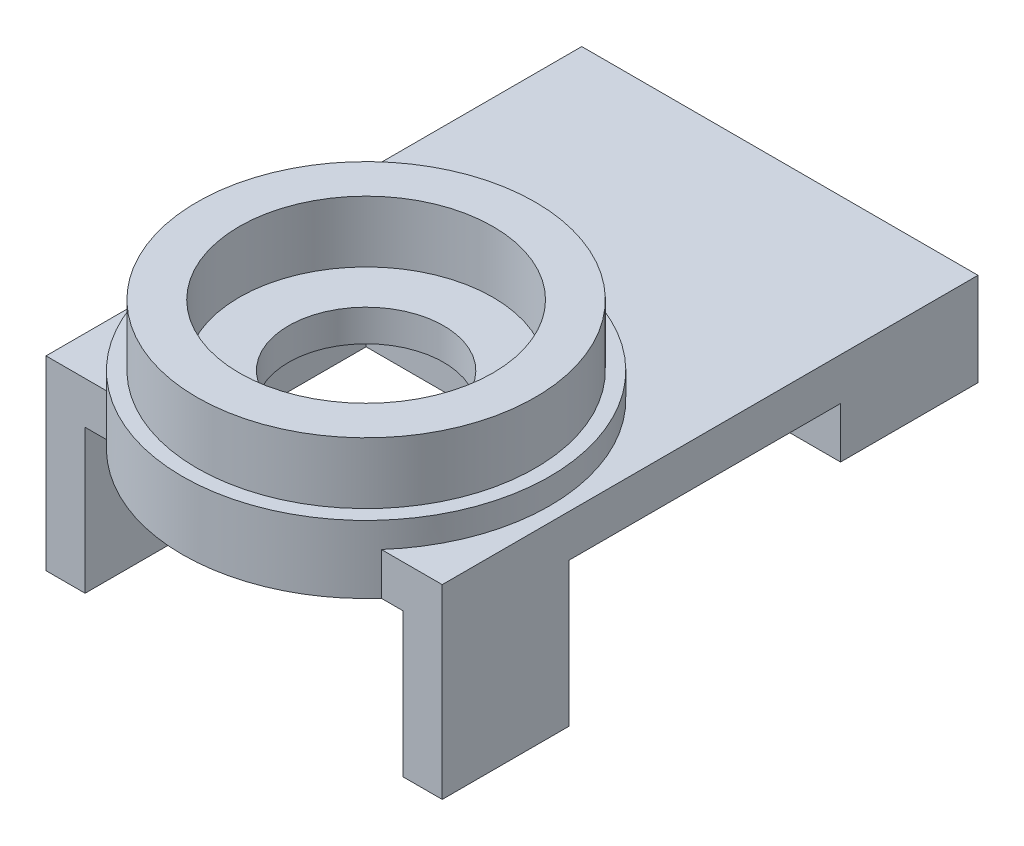
SolidWorks part; units mm, degrees
ref_plane "Front Plane" through (0, 0, 0) normal (0, 0, 1) x (1, 0, 0)
ref_plane "Top Plane" through (0, 0, 0) normal (0, 1, 0) x (1, 0, 0)
ref_plane "Right Plane" through (0, 0, 0) normal (1, 0, 0) x (0, 0, -1)
sketch "Sketch2" plane through (0, 0, 0) normal (0, 1, 0) x (1, 0, 0)
  line L1 (-2.1351, -6.1488) -> (6.2049, -6.1488)
  line L2 (-2.1351, -6.1488) -> (-2.1351, 2.1912)
  line L3 (-2.1351, 2.1912) -> (6.2049, 2.1912)
  line L4 (6.2049, -6.1488) -> (6.2049, 2.1912)
  dimension "D1" = 8.34
extrude "Boss-Extrude2" add sketch "Sketch2" along normal blind 1.5
sketch "Sketch3" plane through (0, 1.5, 0) normal (0, 1, 0) x (1, 0, 0)
  line L0 (2.0349, 2.1912) -> (2.0349, -6.1488)
  line L1 (6.2049, 2.1912) -> (-2.1351, 2.1912) construction
  line L2 (-2.1351, -6.1488) -> (6.2049, -6.1488) construction
  circle A0 centre (2.0349, -1.9788) radius 3.67
  dimension "as" = 7.34
extrude "Cut-Extrude1" cut sketch "Sketch3" against normal blind 1.5 contours L0 A0 | L0 A0
sketch "Sketch5" plane through (0, 1.5, 0) normal (0, 1, 0) x (1, 0, 0)
  line L0 (-2.1351, 2.1912) -> (-3.6351, 2.1912)
  line L1 (-3.6351, 2.1912) -> (-3.6351, 3.6912)
  line L2 (6.2049, -6.1488) -> (6.2049, -7.6488)
  line L3 (6.2049, -7.6488) -> (7.7049, -7.6488)
  line L5 (-3.6351, 3.6912) -> (7.7049, 3.6912)
  line L6 (-3.6351, 3.6912) -> (-3.6351, -7.6488)
  line L7 (-3.6351, -7.6488) -> (7.7049, -7.6488)
  line L8 (7.7049, 3.6912) -> (7.7049, -7.6488)
  line M6 (-2.1351, 2.1912) -> (-2.1351, -6.1488)
  line M7 (-2.1351, -6.1488) -> (6.2049, -6.1488)
  line M8 (6.2049, -6.1488) -> (6.2049, 2.1912)
  line M9 (6.2049, 2.1912) -> (-2.1351, 2.1912)
  dimension "D1" = 1.5
extrude "Boss-Extrude4" add sketch "Sketch5" against normal blind 3.2 contours L6 L7 L2 L0 M7 M6 | L8 L5 L1 L0 L2 L3 M9 M8
sketch "Sketch6" plane through (0, 1.5, 0) normal (0, 1, 0) x (1, 0, 0)
  line L1 (-3.6351, 3.6912) -> (7.7049, 3.6912)
  line L2 (-3.6351, 3.6912) -> (-3.6351, -7.6488)
  line L3 (-3.6351, -7.6488) -> (7.7049, -7.6488)
  line L4 (7.7049, 3.6912) -> (7.7049, -7.6488)
  circle A0 centre (2.0349, -1.9788) radius 8.685
  dimension "D1" = 17.37
extrude "Boss-Extrude5" add sketch "Sketch6" against normal blind 3.2
sketch "Sketch8" plane through (0, 1.5, 0) normal (0, 1, 0) x (1, 0, 0)
  line L0 (2.0349, 1.6912) -> (2.0349, -5.6488)
  circle A0 centre (2.0349, -1.9788) radius 3.67 construction
  circle A1 centre (2.0349, -1.9788) radius 6
  circle A2 centre (2.0349, -1.9788) radius 8
  dimension "D1" = 12
  dimension "D2" = 16
extrude "Boss-Extrude6" add sketch "Sketch8" along normal blind 2.9 contours A2 A1
sketch "Sketch10" plane through (0, -1.7, 0) normal (0, -1, 0) x (1, 0, 0)
  line L0 (6.2049, -2.1912) -> (6.2049, -17.5912)
  line L1 (6.2049, 6.1488) -> (11.4049, 6.1488)
  line L2 (-2.1351, 6.1488) -> (-2.1351, 7.7488)
  line L3 (-2.1351, 6.1488) -> (-7.3351, 6.1488)
  line L5 (-7.3351, 7.7488) -> (-7.3351, 6.1488)
  line L6 (6.2049, -17.5912) -> (11.4049, -17.5912)
  line L8 (-7.3351, 7.7488) -> (11.4049, 7.7488)
  line L9 (-7.3351, 7.7488) -> (-7.3351, -17.5912)
  line L10 (-7.3351, -17.5912) -> (11.4049, -17.5912)
  line L11 (11.4049, 7.7488) -> (11.4049, -17.5912)
  circle A0 centre (2.0349, 1.9788) radius 8.685
  circle M10 centre (2.0349, 1.9788) radius 8.685
  dimension "D1" = 15.4
  dimension "D2" = 5.2
  dimension "D3" = 1.6
extrude "Boss-Extrude7" add sketch "Sketch10" against normal blind 2 contours L9 L10 L0 L3 M10 | L8 L5 L3 M10 | L11 L8 L1 M10 | L11 L1 L0 L6 M10
sketch "Sketch11" plane through (0, -1.7, 0) normal (0, -1, 0) x (1, 0, 0)
  line L0 (11.4049, 7.7488) -> (11.4049, -17.5912) construction
  line L1 (-7.3351, -17.5912) -> (11.4049, -17.5912)
  line L2 (-7.3351, -17.5912) -> (-7.3351, -11.0912)
  line L3 (-7.3351, -11.0912) -> (11.4049, -11.0912)
  line L4 (11.4049, -17.5912) -> (11.4049, -11.0912)
  dimension "D1" = 6.5
extrude "Boss-Extrude8" add sketch "Sketch11" along normal blind 2.4
sketch "Sketch12" plane through (0, -1.7, 0) normal (0, -1, 0) x (1, 0, 0)
  line L1 (-7.3351, 7.7488) -> (-5.4851, 7.7488)
  line L2 (-7.3351, 7.7488) -> (-7.3351, 1.7488)
  line L3 (-7.3351, 1.7488) -> (-5.4851, 1.7488)
  line L4 (-5.4851, 7.7488) -> (-5.4851, 1.7488)
  line L5 (11.4049, 7.7488) -> (9.5549, 7.7488)
  line L6 (11.4049, 7.7488) -> (11.4049, 1.7488)
  line L7 (11.4049, 1.7488) -> (9.5549, 1.7488)
  line L8 (9.5549, 7.7488) -> (9.5549, 1.7488)
  dimension "D1" = 6
  dimension "D2" = 1.85
extrude "Boss-Extrude9" add sketch "Sketch12" along normal blind 6.8
